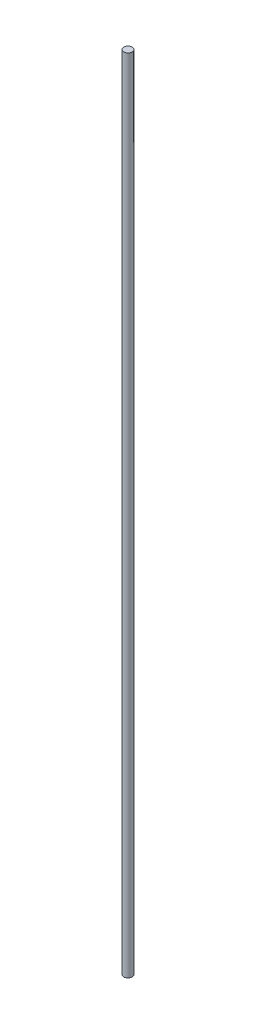
SolidWorks part; units mm, degrees
ref_plane "Front Plane" through (0, 0, 0) normal (0, 0, 1) x (1, 0, 0)
ref_plane "Top Plane" through (0, 0, 0) normal (0, 1, 0) x (1, 0, 0)
ref_plane "Right Plane" through (0, 0, 0) normal (1, 0, 0) x (0, 0, -1)
sketch "Sketch2" plane through (0, 0, 0) normal (0, 1, 0) x (1, 0, 0)
  circle A0 centre (0, 0) radius 3.175
  dimension "D1" = 6.35
extrude "Boss-Extrude1" add sketch "Sketch2" along normal blind 593.725
